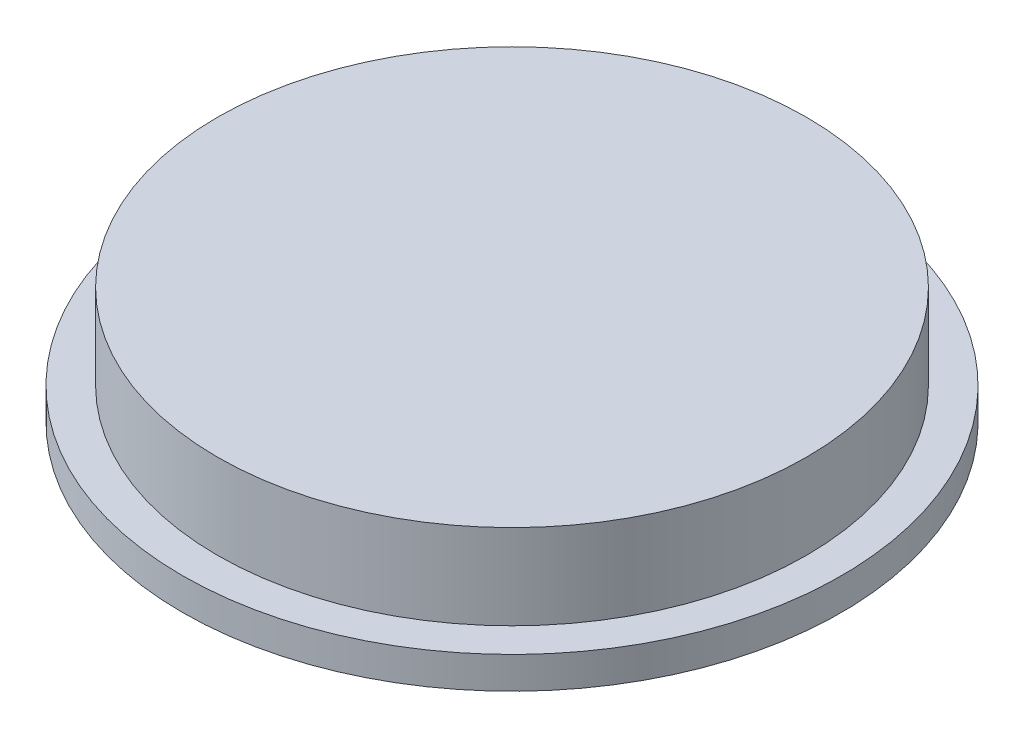
SolidWorks part; units mm, degrees
ref_plane "Alzado" through (0, 0, 0) normal (0, 0, 1) x (1, 0, 0)
ref_plane "Planta" through (0, 0, 0) normal (0, 1, 0) x (1, 0, 0)
ref_plane "Vista lateral" through (0, 0, 0) normal (1, 0, 0) x (0, 0, -1)
sketch "Croquis2" plane through (0, 0, 0) normal (0, 0, 1) x (1, 0, 0)
  line L0 (0, 0) -> (-15.5, 0)
  line L1 (8.525, 0) -> (-8.525, 0) construction
  line L2 (-15.5, 0) -> (-15.5, 1.5)
  line L3 (-15.5, 1.5) -> (-13.85, 1.5)
  line L4 (-13.85, 1.5) -> (-13.85, 5.5)
  line L5 (-13.85, 5.5) -> (0, 5.5)
  line L6 (0, -3.025) -> (0, 3.025) construction
  line L7 (0, 5.5) -> (0, 0)
  line L8 (0, 5.5) -> (0, 0) construction
  dimension "D1" = 13.85
  dimension "D2" = 4
  dimension "D3" = 1.5
  dimension "D4" = 15.5
revolve "Revolución1" add sketch "Croquis2" angle 360 about L8
